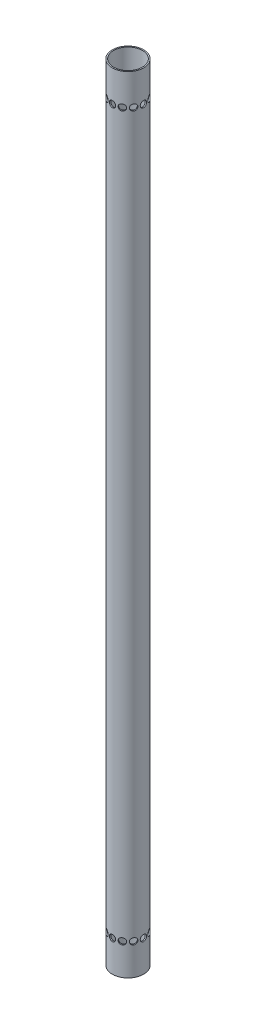
SolidWorks part; units mm, degrees
material "Copper"
ref_plane "Front Plane" through (0, 0, 0) normal (0, 0, 1) x (1, 0, 0)
ref_plane "Top Plane" through (0, 0, 0) normal (0, 1, 0) x (1, 0, 0)
ref_plane "Right Plane" through (0, 0, 0) normal (1, 0, 0) x (0, 0, -1)
sketch "Sketch1" plane through (0, 0, 0) normal (0, 1, 0) x (1, 0, 0)
  circle A0 centre (0, 0) radius 25
  circle A1 centre (0, 0) radius 23
  dimension "D1" = 50
  dimension "D2" = 2
extrude "Boss-Extrude1" add sketch "Sketch1" along normal blind 1250
ref_plane "Plane1" through (-25, 0, 0) normal (-1, 0, 0) x (0, 0, 1)
sketch "Sketch6" plane through (-25, 0, 0) normal (-1, 0, 0) x (0, 0, 1)
  line L0 (0, 0) -> (0, 50)
  line L1 (0, 1250) -> (0, 1200)
  line L2 (25, 1250) -> (-25, 1250) construction
  circle A0 centre (0, 50) radius 5
  circle A1 centre (0, 1200) radius 5
  dimension "D1" = 10
  dimension "D3" = 10
  dimension "D2" = 50
  dimension "D4" = 50
extrude "Cut-Extrude1" cut sketch "Sketch6" against normal blind 76 contours A0 | A1
pattern_circular "CirPattern2" count 6 every 30 about axis through (0, 1250, 0) along (0, -1, 0) of "Cut-Extrude1"
